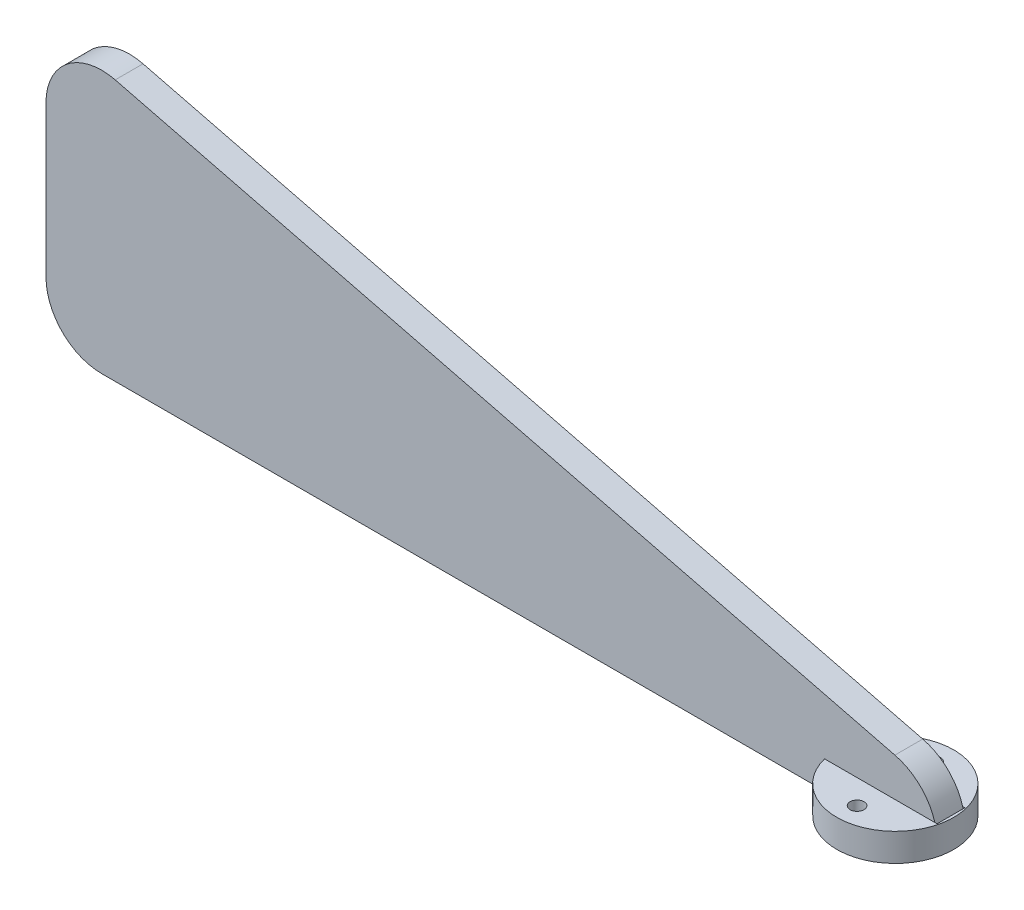
SolidWorks part; units mm, degrees
ref_plane "정면" through (0, 0, 0) normal (0, 0, 1) x (1, 0, 0)
ref_plane "윗면" through (0, 0, 0) normal (0, 1, 0) x (1, 0, 0)
ref_plane "우측면" through (0, 0, 0) normal (1, 0, 0) x (0, 0, -1)
sketch "스케치1" plane through (0, 0, 0) normal (0, 0, 1) x (1, 0, 0)
  line L0 (0, 0) -> (73.353, 0) construction
  line L1 (0, 0) -> (0, 71.7589) construction
  line L2 (0, 10) -> (0, 37.1922)
  line L3 (10, 0) -> (160, 0)
  line L4 (160, 0) -> (160, 2.1922)
  line L5 (152.4254, 11.8937) -> (12.4254, 46.8937)
  arc A0 (160, 2.1922) -> (152.4254, 11.8937) centre (150, 2.1922) ccw
  arc A1 (0, 10) -> (10, 0) centre (10, 10) ccw
  arc A2 (0, 37.1922) -> (12.4254, 46.8937) centre (10, 37.1922) cw
  point P9 (160, 10)
  point P15 (0, 50)
  dimension "D4" = 10
  dimension "D1" = 50
  dimension "D2" = 160
  dimension "D3" = 10
extrude "보스-돌출1" add sketch "스케치1" along normal blind 5
sketch "스케치2" plane through (0, 0, 0) normal (0, -1, 0) x (1, 0, 0)
  line L0 (100.3305, 2.4825) -> (160, 2.5) construction
  line L1 (160, 2.5) -> (71.5478, 2.5) construction
  line L2 (150, 2.5) -> (150, 10.62) construction
  line L3 (150, 2.5) -> (150, -6.4724) construction
  line L4 (10, 0) -> (160, 0)
  line L5 (160, 0) -> (160, 5)
  line L6 (160, 5) -> (10, 5)
  line L7 (10, 5) -> (10, 0)
  line L8 (10, 0) -> (160, 0)
  line L9 (160, 0) -> (160, 5)
  line L10 (160, 5) -> (10, 5)
  line L11 (10, 5) -> (10, 0)
  circle A0 centre (150, 2.5) radius 2.5
  circle A2 centre (150, 2.5) radius 10.5
  circle A3 centre (150, 9.37) radius 1.25
  circle A4 centre (150, -4.37) radius 1.25
  dimension "D2" = 5
  dimension "D4" = 21
  dimension "D6" = 2.5
  dimension "D3" = 10
  dimension "D5" = 8.12
  dimension "D1" = 0
extrude "보스-돌출4" add sketch "스케치2" against normal blind 5 contours L10 A2 | L8 A2
